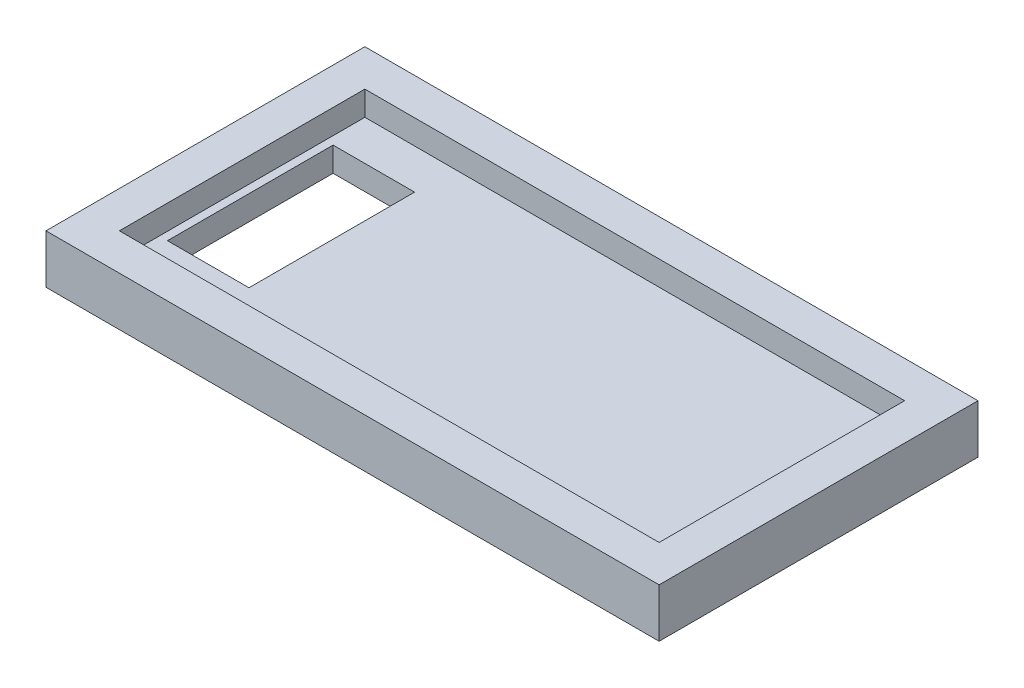
SolidWorks part; units mm, degrees
ref_plane "Plano frontal" through (0, 0, 0) normal (0, 0, 1) x (1, 0, 0)
ref_plane "Plano superior" through (0, 0, 0) normal (0, 1, 0) x (1, 0, 0)
ref_plane "Plano direito" through (0, 0, 0) normal (1, 0, 0) x (0, 0, -1)
sketch "Esboço1" plane through (0, 0, 0) normal (0, 1, 0) x (1, 0, 0)
  line L5 (-18.805, -9.78) -> (18.805, -9.78)
  line L6 (-18.805, -9.78) -> (-18.805, 9.78)
  line L7 (-18.805, 9.78) -> (18.805, 9.78)
  line L8 (18.805, -9.78) -> (18.805, 9.78)
  line L9 (-18.805, -9.78) -> (18.805, 9.78) construction
  line L10 (-18.805, 9.78) -> (18.805, -9.78) construction
  point P0 (0, 0)
  dimension "D1" = 19.56
  dimension "D2" = 37.61
extrude "Base" add sketch "Esboço1" along normal blind 3
sketch "Esboço4" plane through (0, 0, 0) normal (0, 1, 0) x (1, 0, 0)
  line L1 (-16.555, -7.53) -> (16.555, -7.53)
  line L2 (-16.555, -7.53) -> (-16.555, 7.53)
  line L3 (-16.555, 7.53) -> (16.555, 7.53)
  line L4 (16.555, -7.53) -> (16.555, 7.53)
  line L5 (-16.555, -7.53) -> (16.555, 7.53) construction
  line L6 (-16.555, 7.53) -> (16.555, -7.53) construction
  point P0 (0, 0)
  dimension "D1" = 33.11
  dimension "D2" = 15.06
extrude "Espaço Sensor" cut sketch "Esboço4" against normal blind 1.5 from surface at 3 starting at face at (0, 3, 0)
sketch "Esboço5" plane through (0, 0, 0) normal (0, 1, 0) x (1, 0, 0)
  line L0 (16.555, 0) -> (-13.555, 0) construction
  line L1 (16.555, -7.53) -> (16.555, 7.53) construction
  line L3 (-11.055, -5.08) -> (-16.055, -5.08)
  line L4 (-11.055, -5.08) -> (-11.055, 5.08)
  line L5 (-11.055, 5.08) -> (-16.055, 5.08)
  line L6 (-16.055, -5.08) -> (-16.055, 5.08)
  line L7 (-11.055, -5.08) -> (-16.055, 5.08) construction
  line L8 (-11.055, 5.08) -> (-16.055, -5.08) construction
  dimension "D1" = 30.11
  dimension "D2" = 10.16
  dimension "D3" = 5
extrude "Recorte Conectores" cut sketch "Esboço5" against normal through all from surface at 1.5 starting at face at (0, 1.5, 0)
sketch "Esboço6" plane through (0, 0, 0) normal (0, 1, 0) x (1, 0, 0)
  line L0 (0, -9.78) -> (0, -8.655) construction
  line L1 (-18.805, -9.78) -> (18.805, -9.78) construction
  line L2 (-17.68, -8.655) -> (17.68, -8.655) construction
  line L3 (18.805, 0) -> (17.68, 0) construction
  line L4 (18.805, -9.78) -> (18.805, 9.78) construction
  line L5 (17.68, -8.655) -> (17.68, 8.655) construction
  line L6 (-17.68, 8.655) -> (17.68, 8.655) construction
  line L7 (-17.68, -8.655) -> (-17.68, 8.655) construction
  circle A0 centre (-17.68, -8.655) radius 0.75
  circle A1 centre (17.68, -8.655) radius 0.75
  circle A2 centre (17.68, 8.655) radius 0.75
  circle A3 centre (-17.68, 8.655) radius 0.75
  dimension "D1" = 1.5
  dimension "D2" = 1.125
extrude "Corte-extrusão3" cut sketch "Esboço6" along normal blind 2
